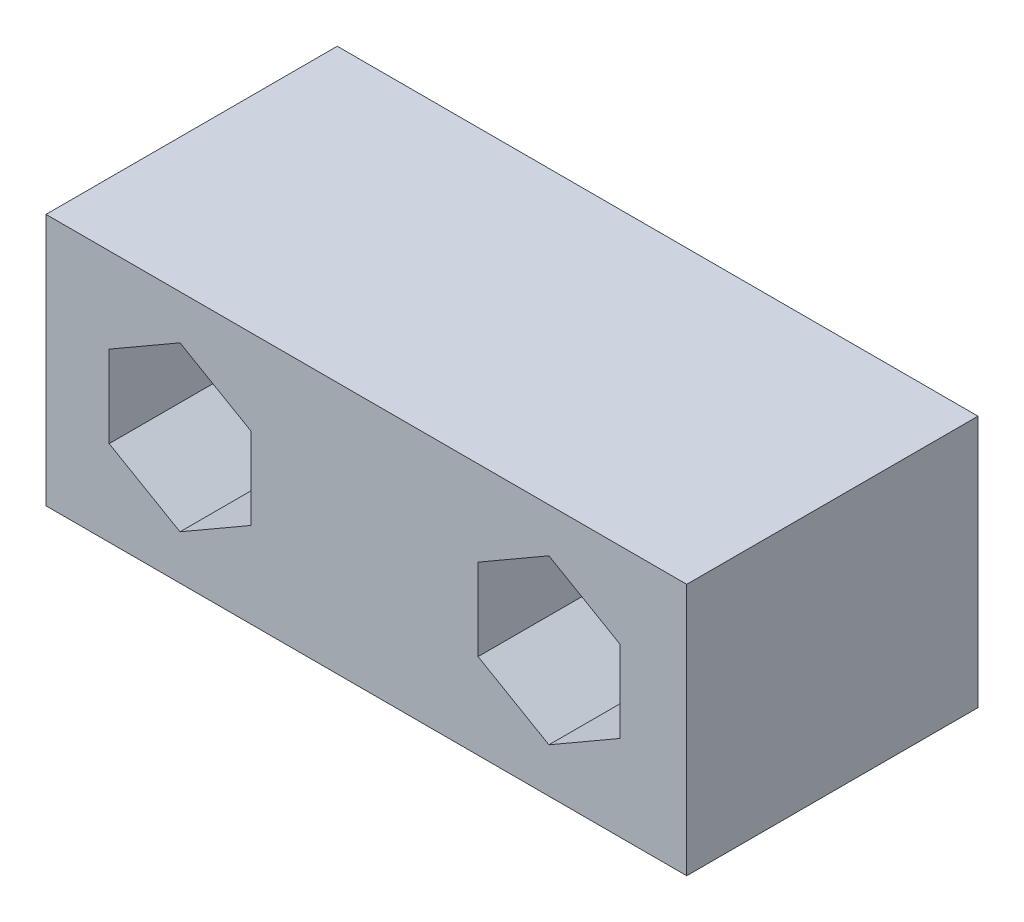
SolidWorks part; units mm, degrees
ref_plane "Front Plane" through (0, 0, 0) normal (0, 0, 1) x (1, 0, 0)
ref_plane "Top Plane" through (0, 0, 0) normal (0, 1, 0) x (1, 0, 0)
ref_plane "Right Plane" through (0, 0, 0) normal (1, 0, 0) x (0, 0, -1)
ref_plane "Plane1" through (0, 0, 7.5) normal (0, 0, 1) x (1, 0, 0)
sketch "Sketch1" plane through (0, 0, 7.5) normal (0, 0, 1) x (1, 0, 0)
  line L0 (-47.65, -2.0992) -> (-47.65, 2.1155)
  line L1 (-47.65, 2.1155) -> (-44, 4.2228)
  line L2 (-44, 4.2228) -> (-40.35, 2.1155)
  line L3 (-40.35, 2.1155) -> (-40.35, -2.0992)
  line L4 (-40.35, -2.0992) -> (-44, -4.2065)
  line L5 (-44, -4.2065) -> (-47.65, -2.0992)
  line L6 (-28.65, -2.0992) -> (-28.65, 2.1155)
  line L7 (-28.65, 2.1155) -> (-25, 4.2228)
  line L8 (-25, 4.2228) -> (-21.35, 2.1155)
  line L9 (-21.35, 2.1155) -> (-21.35, -2.0992)
  line L10 (-21.35, -2.0992) -> (-25, -4.2065)
  line L11 (-25, -4.2065) -> (-28.65, -2.0992)
  line L12 (-50.9022, 6.5) -> (-50.9022, -6.5)
  line L13 (-50.9022, -6.5) -> (-17.9022, -6.5)
  line L14 (-17.9022, -6.5) -> (-17.9022, 6.5)
  line L15 (-17.9022, 6.5) -> (-50.9022, 6.5)
extrude "Boss-Extrude1" add sketch "Sketch1" against normal blind 15
sketch3d "3DSketch4" plane through (0, 0, 0) normal (0, 0, 1) x (1, 0, 0)
  dimension "D1" = 16.5
